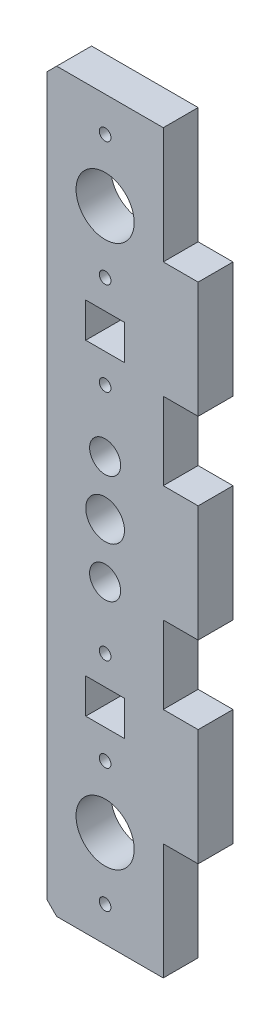
SolidWorks part; units mm, degrees
ref_plane "Front Plane" through (0, 0, 0) normal (0, 0, 1) x (1, 0, 0)
ref_plane "Top Plane" through (0, 0, 0) normal (0, 1, 0) x (1, 0, 0)
ref_plane "Right Plane" through (0, 0, 0) normal (1, 0, 0) x (0, 0, -1)
sketch "Model" plane through (0, 0, 0) normal (0, 0, 1) x (1, 0, 0)
  line L0 (0, 175) -> (-30, 175) construction
  line L1 (-15, 175) -> (-15, -20.1815) construction
  line L2 (-15, 25) -> (0, 25) construction
  line L3 (-27.5, 190) -> (-30, 187.5)
  line L4 (-27.5, 0) -> (-30, 2.5)
  line L5 (27.5425, 149) -> (-15, 149) construction
  line L6 (27.5425, 149) -> (27.5425, 125) construction
  line L7 (27.5425, 125) -> (-15, 125) construction
  line L8 (-15, 137) -> (27.5425, 137) construction
  line L30 (-27.5, 0) -> (0, 0)
  line L39 (-30, 2.5) -> (-30, 187.5)
  line L40 (-27.5, 190) -> (0, 190)
  line L41 (0, 0) -> (0, 30)
  line L42 (-30, 95) -> (9, 95) construction
  line L43 (0, 110) -> (0, 130)
  line L44 (0, 110) -> (9, 110)
  line L45 (0, 160) -> (9, 160)
  line L46 (0, 80) -> (9, 80)
  line L47 (9, 110) -> (9, 80)
  line L54 (9, 160) -> (9, 130)
  line L55 (0, 130) -> (9, 130)
  line L56 (0, 60) -> (9, 60)
  line L57 (9, 60) -> (9, 30)
  line L58 (0, 30) -> (9, 30)
  line L59 (0, 160) -> (0, 190)
  line L60 (0, 60) -> (0, 80)
  line L61 (-20, 48.5) -> (-20, 57.5)
  line L62 (-20, 141.5) -> (-10, 141.5)
  line L63 (-20, 141.5) -> (-20, 132.5)
  line L64 (-20, 132.5) -> (-10, 132.5)
  line L65 (-10, 141.5) -> (-10, 132.5)
  line L66 (-20, 141.5) -> (-10, 132.5) construction
  line L67 (-20, 132.5) -> (-10, 141.5) construction
  line L68 (-20, 57.5) -> (-10, 57.5)
  line L69 (-10, 48.5) -> (-10, 57.5)
  line L70 (-20, 48.5) -> (-10, 48.5)
  circle A2 centre (-15, 109) radius 4
  circle A3 centre (-15, 165) radius 7.5
  circle A4 centre (-15, 25) radius 7.5
  circle A5 centre (-15, 95) radius 5
  circle A6 centre (-15, 81) radius 4
  circle A7 centre (-15, 41) radius 1.5
  circle A8 centre (-15, 9) radius 1.5
  circle A9 centre (-15, 181) radius 1.5
  circle A10 centre (-15, 149) radius 1.5
  circle A11 centre (-15, 125) radius 1.5
  circle A12 centre (-15, 65) radius 1.5
  point P8 (-15, 175)
  point P56 (9, 95)
  point P61 (-15, 137)
  dimension "D13" = 15
  dimension "D10" = 8
  dimension "D12" = 3
  dimension "D8" = 10
  dimension "D4" = 9
  dimension "D6" = 30
  dimension "D7" = 190
  dimension "D19" = 9
  dimension "D22" = 20
  dimension "D24" = 10
  dimension "D5" = 30
  dimension "D11" = 16
  dimension "D9" = 14
  dimension "D14" = 30
  dimension "D15" = 70
  dimension "D3" = 2.5
  dimension "D16" = 135
  dimension "D17" = 2
  dimension "D18" = 2
extrude "Boss-Extrude1" add sketch "Model" along normal blind 9
equation "\"material-thickness\" = 9mm"
equation "\"tab-width-large\" = 30mm ' Width of the large version of the Tab"
equation "\"plate-supporttab-gapheight\" = 20mm"
equation "\"linear-bar-dia\" = 8mm ' Diameter of the metal slide bar used on the X Axis"
equation "\"linear-thread-dia\" = 8mm ' Diameter of the metal threaded rod used on the X Axis"
equation "\"linear-thread-nut-dia\" = 12.8mm ' Outer Diameter of the Nut used on the X Axis, typically M8 = 10mm"
equation "\"linear-bar-bearingouter-dia\" = 15mm ' Diameter of the outer side of the bearing"
equation "\"D4@Model\"=\"material-thickness\""
equation "\"D13@Model\"=\"linear-bar-bearingouter-dia\""
equation "\"D19@Model\"=\"material-thickness\""
equation "\"D6@Model\"=\"tab-width-large\""
equation "\"D1@Boss-Extrude1\"=\"material-thickness\""
equation "\"D22@Model\"=\"plate-supporttab-gapheight\""
equation "\"D10@Model\"=\"linear-bar-dia\""
equation "\"D8@Model\"=\"linear-thread-dia\" +2"
